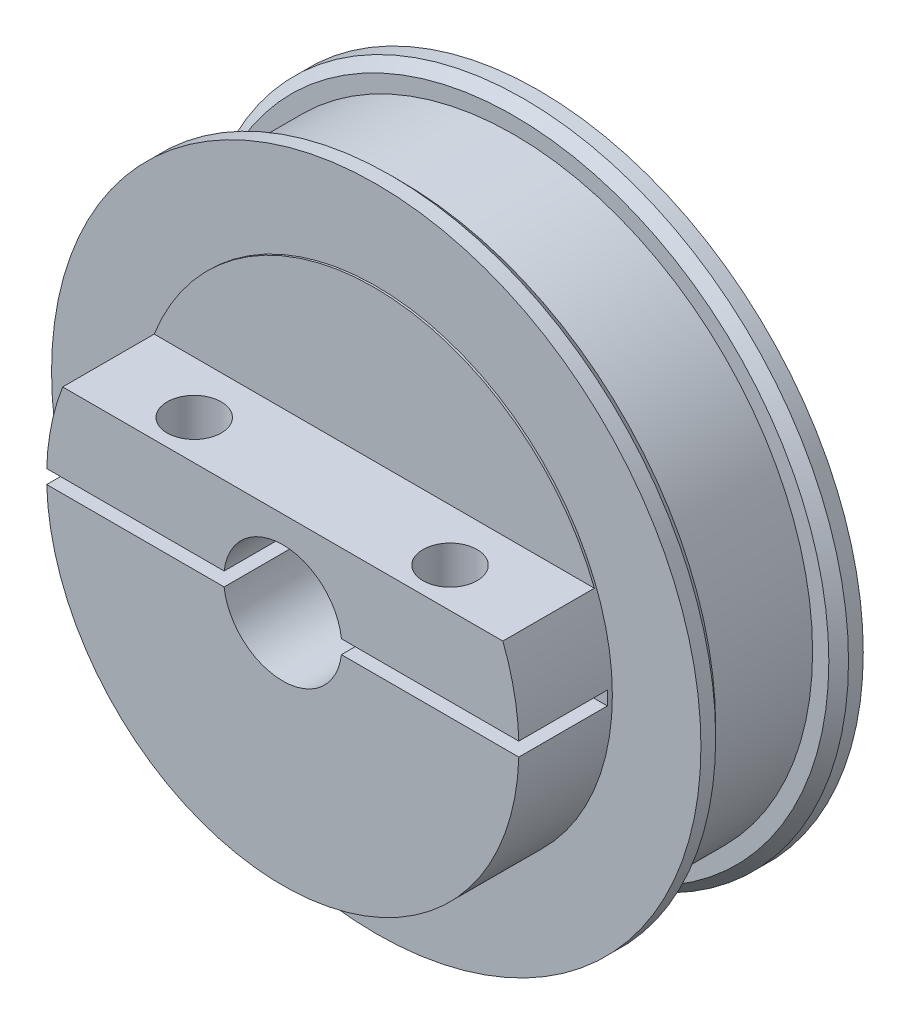
SolidWorks part; units mm, degrees
material "SKD11淬火HRC56-60"
ref_plane "前基準面" through (0, 0, 0) normal (0, 0, 1) x (1, 0, 0)
ref_plane "上基準面" through (0, 0, 0) normal (0, 1, 0) x (1, 0, 0)
ref_plane "右基準面" through (0, 0, 0) normal (1, 0, 0) x (0, 0, -1)
sketch "草图1" plane through (0, 0, 0) normal (0, 0, 1) x (1, 0, 0)
  circle A0 centre (0, 0) radius 33
  dimension "D1" = 66
extrude "凸台-拉伸1" add sketch "草图1" along normal blind 2.5
sketch "草图2" plane through (0, 0, 2.5) normal (0, 0, 1) x (1, 0, 0)
  circle A0 centre (0, 0) radius 30.35
  dimension "D1" = 60.7
extrude "凸台-拉伸2" add sketch "草图2" along normal blind 11.5
sketch "草图3" plane through (0, 0, 14) normal (0, 0, 1) x (1, 0, 0)
  circle A1 centre (0, 0) radius 33
  circle A2 centre (0, 0) radius 33
  dimension "D1" = 0
extrude "凸台-拉伸3" add sketch "草图3" along normal blind 2.5
sketch "草图4" plane through (0, 0, 16.5) normal (0, 0, 1) x (1, 0, 0)
  circle A0 centre (0, 0) radius 24
  dimension "D1" = 48
extrude "凸台-拉伸4" add sketch "草图4" along normal blind 9.5
chamfer "倒角1" distance 1 angle 45 2 edges at (33, 0, 2.5) (33, 0, 14)
sketch "草图5" plane through (0, 0, 26) normal (0, 0, 1) x (1, 0, 0)
  circle A0 centre (0, 0) radius 6
  dimension "D1" = 12
extrude "切除-拉伸1" cut sketch "草图5" against normal through all
sketch "草图6" plane through (0, 0, 26) normal (0, 0, 1) x (1, 0, 0)
  line L0 (0, 0) -> (45.5864, 0) construction
  line L1 (-25, 0.7) -> (25, 0.7)
  line L2 (-25, 0.7) -> (-25, -0.7)
  line L3 (-25, -0.7) -> (25, -0.7)
  line L4 (25, 0.7) -> (25, -0.7)
  line L5 (0, 0) -> (0, -18.6563) construction
  dimension "D1" = 1.4
  dimension "D2" = 50
extrude "切除-拉伸2" cut sketch "草图6" against normal blind 9
sketch "草图7" plane through (0, 0.7, 0) normal (0, -1, 0) x (1, 0, 0)
  line L0 (0, 0) -> (0, 31.9292) construction
  line L1 (-33, 0) -> (33, 0) construction
  line L2 (23.9898, 26) -> (-23.9898, 26) construction
  circle A0 centre (-13, 22) radius 2.75
  circle A1 centre (13, 22) radius 2.75
  dimension "D1" = 4
  dimension "D2" = 5.5
  dimension "D3" = 26
extrude "切除-拉伸3" cut sketch "草图7" against normal blind 8
sketch "草图8" plane through (0, 8.7, 0) normal (0, -1, 0) x (1, 0, 0)
  circle A0 centre (-13, 22) radius 5
  circle A1 centre (13, 22) radius 5
  dimension "D1" = 10
extrude "切除-拉伸4" cut sketch "草图8" against normal through all
hole_wizard "M5 螺纹孔1" positions "草图10" profile "草图11" tap size "M5" standard "ISO" end condition through all
sketch "草图10" plane through (0, -0.7, 0) normal (0, 1, 0) x (-1, 0, 0)
  point P0 (13, 22)
  point P5 (-13, 22)
sketch "草图11" plane through (-13, -0.7, 22) normal (1, 0, 0) x (0, 0, 1)
  line L0 (0, 0) -> (0, 32.3)
  line L1 (0, 32.3) -> (2.1, 32.3)
  line L2 (2.1, 32.3) -> (2.1, 0)
  line L5 (2.1, 0) -> (0, 0)
  line L11 (0, -6.35) -> (0, 107.95) construction
  dimension "通孔螺纹孔钻头直径" = 4.2
  dimension "通孔螺纹孔钻头深度" = 32.3
cosmetic thread "孔螺蚊线1" parameters "D2"=5
cosmetic thread "孔螺蚊线2" parameters "D2"=5
sketch "草图12" plane through (0, 0, 26) normal (0, 0, 1) x (1, 0, 0)
  line L0 (0, 0) -> (0, 19.0076) construction
  line L1 (-18, 8.7) -> (-8, 8.7)
  line L2 (-18, 8.7) -> (-18, 22.7)
  line L3 (-18, 22.7) -> (-8, 22.7)
  line L4 (-8, 8.7) -> (-8, 22.7)
  line L5 (-13, 8.7) -> (-13, 6.141) construction
  line L6 (-16, 8.7) -> (-10, 8.7) construction
  line L7 (8, 8.7) -> (8, 22.7)
  line L8 (18, 22.7) -> (8, 22.7)
  line L9 (18, 8.7) -> (18, 22.7)
  line L10 (18, 8.7) -> (8, 8.7)
  dimension "D1" = 10
  dimension "D2" = 14
extrude "切除-拉伸5" cut sketch "草图12" against normal blind 4
sketch "草图13" plane through (0, 0, 26) normal (0, 0, 1) x (1, 0, 0)
  line L0 (8, 8.7) -> (18, 8.7) construction
  line L1 (-38.9537, 25.2764) -> (33.5342, 25.2764)
  line L2 (-38.9537, 25.2764) -> (-38.9537, 8.7)
  line L3 (-38.9537, 8.7) -> (33.5342, 8.7)
  line L4 (33.5342, 25.2764) -> (33.5342, 8.7)
extrude "切除-拉伸6" cut sketch "草图13" against normal blind 9.3
